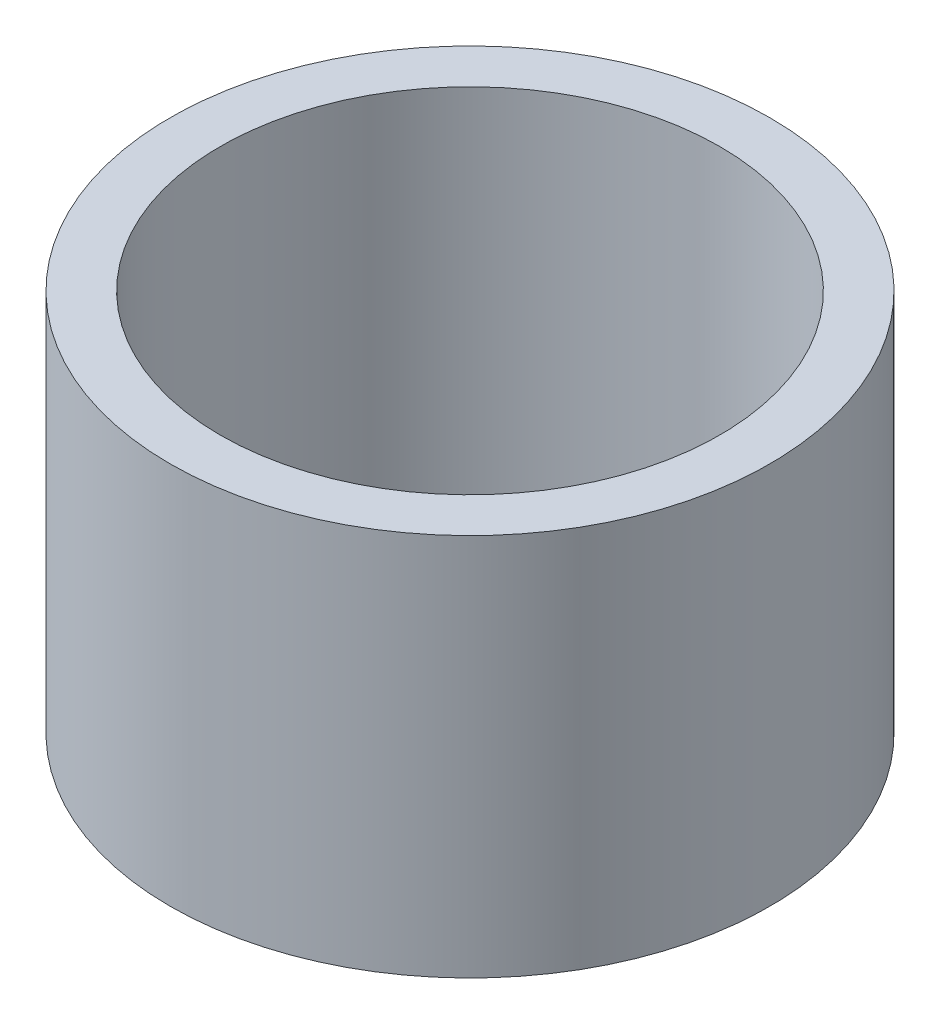
SolidWorks part; units mm, degrees
ref_plane "Front Plane" through (0, 0, 0) normal (0, 0, 1) x (1, 0, 0)
ref_plane "Top Plane" through (0, 0, 0) normal (0, 1, 0) x (1, 0, 0)
ref_plane "Right Plane" through (0, 0, 0) normal (1, 0, 0) x (0, 0, -1)
sketch "Sketch1" plane through (0, 0, 0) normal (0, 1, 0) x (1, 0, 0)
  circle A0 centre (0, 0) radius 15
  circle A1 centre (0, 0) radius 18
  dimension "D1" = 30
  dimension "D2" = 36
extrude "Boss-Extrude1" add sketch "Sketch1" along normal blind 23
